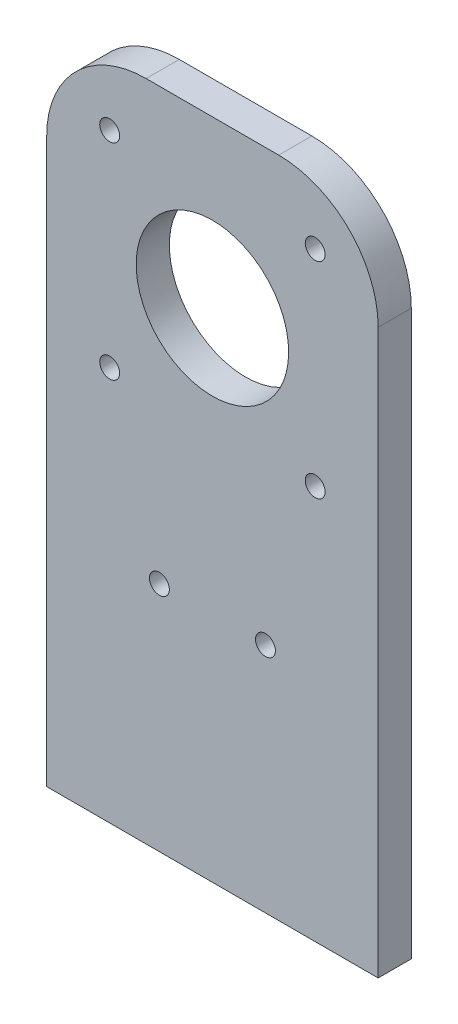
SolidWorks part; units mm, degrees
ref_plane "Front Plane" through (0, 0, 0) normal (0, 0, 1) x (1, 0, 0)
ref_plane "Top Plane" through (0, 0, 0) normal (0, 1, 0) x (1, 0, 0)
ref_plane "Right Plane" through (0, 0, 0) normal (1, 0, 0) x (0, 0, -1)
sketch "Sketch4" plane through (0, 0, 0) normal (0, 0, 1) x (1, 0, 0)
  line L0 (-10.0874, 107.0888) -> (9.9126, 107.0888)
  line L1 (-0.0874, 23.0888) -> (-0.0874, 107.0888) construction
  line L3 (-25.0874, 92.0888) -> (-25.0874, 7.0888)
  line L4 (-25.0874, 7.0888) -> (24.9126, 7.0888)
  line L5 (24.9126, 7.0888) -> (24.9126, 92.0888)
  circle A0 centre (-0.0874, 82.0888) radius 11.5
  circle A1 centre (15.4126, 66.5888) radius 1.5
  circle A2 centre (-15.5874, 66.5888) radius 1.5
  circle A3 centre (15.4126, 97.5888) radius 1.5
  circle A4 centre (-15.5874, 97.5888) radius 1.5
  circle A5 centre (-8.0874, 42.0888) radius 1.5
  circle A6 centre (7.9126, 42.0888) radius 1.5
  arc A7 (9.9126, 107.0888) -> (24.9126, 92.0888) centre (9.9126, 92.0888) cw
  arc A8 (-25.0874, 92.0888) -> (-10.0874, 107.0888) centre (-10.0874, 92.0888) cw
  point P23 (24.9126, 107.0888)
  dimension "D1" = 23
  dimension "D2" = 3
  dimension "D6" = 15
  dimension "D7" = 3
  dimension "D4" = 15.5
  dimension "D5" = 8
  dimension "D8" = 35
  dimension "D9" = 17
  dimension "D10" = 100
extrude "Boss-Extrude1" add sketch "Sketch4" along normal blind 5
